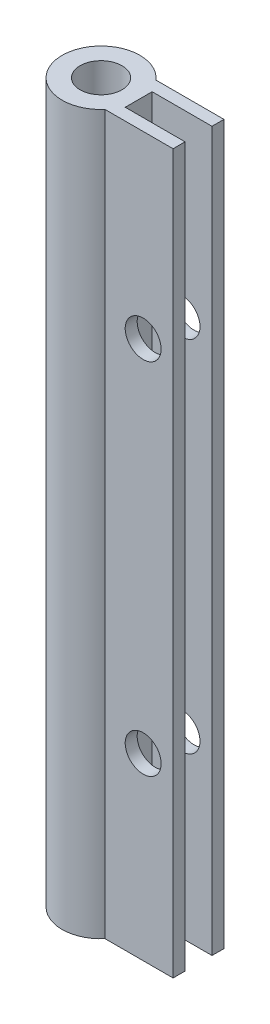
SolidWorks part; units mm, degrees
ref_plane "Front Plane" through (0, 0, 0) normal (0, 0, 1) x (1, 0, 0)
ref_plane "Top Plane" through (0, 0, 0) normal (0, 1, 0) x (1, 0, 0)
ref_plane "Right Plane" through (0, 0, 0) normal (1, 0, 0) x (0, 0, -1)
sketch "Sketch1" plane through (0, 0, 0) normal (0, 1, 0) x (1, 0, 0)
  line L0 (8.1442, -1.125) -> (8.1442, -2.125)
  line L1 (2.459, 2.125) -> (8.1442, 2.125)
  line L3 (2.459, -2.125) -> (8.1442, -2.125)
  line L4 (8.1442, 2.125) -> (8.1442, 1.125)
  line L5 (4.5031, -1.125) -> (8.1442, -2.125) construction
  line L6 (3.1442, 1.125) -> (3.1442, -1.125)
  line L13 (3.1442, 1.125) -> (8.1442, 1.125)
  line L14 (4.5031, 1.125) -> (8.1442, 2.125) construction
  line L15 (3.1442, -1.125) -> (8.1442, -1.125)
  circle A0 centre (0, 0) radius 1.75
  arc A1 (2.459, 2.125) -> (2.459, -2.125) centre (0, 0) ccw
  point P9 (3.25, 0)
  point P12 (0, 0)
  dimension "D1" = 3.5
  dimension "D2" = 6.5
  dimension "D6" = 3.25
  dimension "D3" = 4.25
  dimension "D4" = 5
  dimension "D5" = 2.25
extrude "Boss-Extrude1" add sketch "Sketch1" along normal blind 60
sketch "Sketch2" plane through (0, 0, 2.125) normal (0, 0, 1) x (1, 0, 0)
  line L0 (5.6442, 60) -> (5.6442, 0) construction
  line L4 (8.1442, 60) -> (8.1442, 0) construction
  line L5 (8.1442, 60) -> (8.1442, 0) construction
  line L6 (8.1442, 0) -> (2.459, 0) construction
  line L7 (2.459, 0) -> (2.459, 60) construction
  line L8 (2.459, 60) -> (8.1442, 60) construction
  line L9 (3.1442, 60) -> (3.1442, 0) construction
  circle A2 centre (5.6442, 45) radius 1.5
  circle A3 centre (5.6442, 15) radius 1.5
  dimension "D1" = 2.5
  dimension "D2" = 15
  dimension "D4" = 3
  dimension "D5" = 3
  dimension "D3" = 15
  dimension "D7" = 5
extrude "Cut-Extrude1" cut sketch "Sketch2" against normal blind 60
